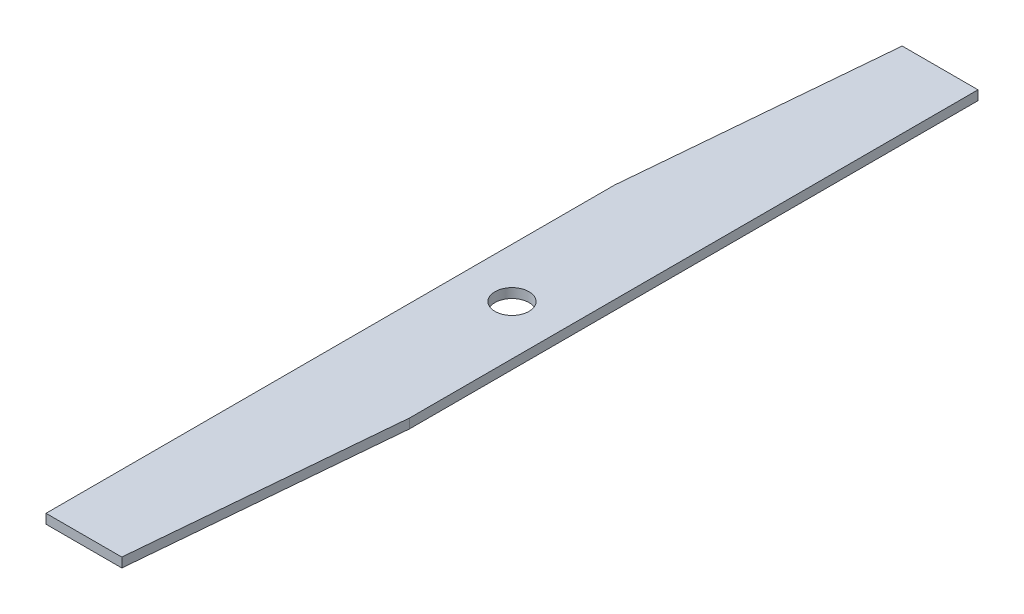
SolidWorks part; units mm, degrees
ref_plane "Front Plane" through (0, 0, 0) normal (0, 0, 1) x (1, 0, 0)
ref_plane "Top Plane" through (0, 0, 0) normal (0, 1, 0) x (1, 0, 0)
ref_plane "Right Plane" through (0, 0, 0) normal (1, 0, 0) x (0, 0, -1)
sketch "Sketch1" plane through (0, 0, 0) normal (0, 1, 0) x (1, 0, 0)
  line L0 (0, 0) -> (0, 190.5)
  line L1 (0, 190.5) -> (7.8481, 279.0529)
  line L2 (7.8481, 279.0529) -> (33.2481, 279.0529)
  line L3 (33.2481, 279.0529) -> (33.2481, 88.5529)
  line L4 (0, 0) -> (25.4, 0)
  line L5 (33.2481, 88.5529) -> (25.4, 0)
  line L6 (0, 190.5) -> (33.2481, 88.5529) construction
  circle A0 centre (16.6241, 139.5265) radius 5.715
  dimension "D7" = 11.43
  dimension "D1" = 190.5
  dimension "D2" = 88.9
  dimension "D3" = 25.4
  dimension "D4" = 190.5
  dimension "D5" = 25.4
  dimension "D6" = 88.9
extrude "Boss-Extrude1" add sketch "Sketch1" along normal blind 3.175 contours L1 L6 A0 L3 L2 | L6 L0 L4 L5 A0
